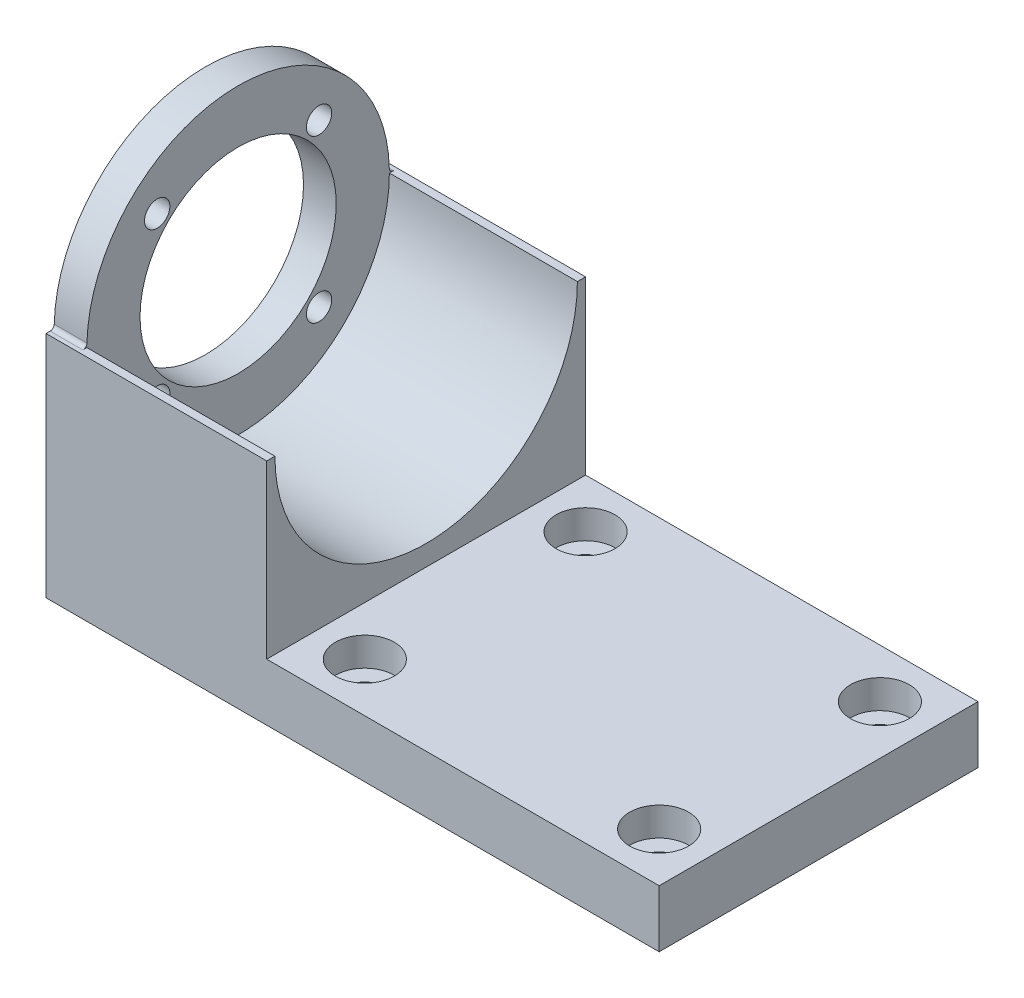
SolidWorks part; units mm, degrees
ref_plane "Plano frontal" through (0, 0, 0) normal (0, 0, 1) x (1, 0, 0)
ref_plane "Plano superior" through (0, 0, 0) normal (0, 1, 0) x (1, 0, 0)
ref_plane "Plano direito" through (0, 0, 0) normal (1, 0, 0) x (0, 0, -1)
sketch "Esboço1" plane through (0, 0, 0) normal (1, 0, 0) x (0, 0, -1)
  circle A0 centre (0, 0) radius 12
  circle A1 centre (0, 0) radius 18.5
  dimension "D1" = 24
  dimension "D2" = 37
extrude "Ressalto-extrusão1" add sketch "Esboço1" along normal blind 4
sketch "Esboço2" plane through (0, 0, 0) normal (-1, 0, 0) x (0, 0, 1)
  line L0 (-19.5, 0) -> (-19.5, -21)
  line L1 (-19.5, -21) -> (19.5, -21)
  line L2 (19.5, -21) -> (19.5, 0)
  line L5 (-19.5, 0) -> (-18.5, 0)
  line L6 (18.5, 0) -> (19.5, 0)
  arc A0 (-18.5, 0) -> (18.5, 0) centre (0, 0) ccw
  dimension "D2" = 37
  dimension "D1" = 39
  dimension "D3" = 21
  dimension "D4" = 1
extrude "Ressalto-extrusão2" add sketch "Esboço2" against normal blind 27
fillet "Filete1" radius 0.5 2 edges at (2, 0, 18.5) (2, 0, -18.5)
sketch "Esboço3" plane through (0, 0, 0) normal (-1, 0, 0) x (0, 0, 1)
  line L0 (19.5, -21) -> (19.5, 0) construction
  line L1 (-19.5, -21) -> (19.5, -21)
  line L2 (-19.5, -21) -> (-19.5, -28)
  line L3 (-19.5, -28) -> (19.5, -28)
  line L4 (19.5, -21) -> (19.5, -28)
  dimension "D1" = 7
extrude "Ressalto-extrusão3" add sketch "Esboço3" against normal blind 75
sketch "Esboço4" plane through (0, -21, 0) normal (0, 1, 0) x (1, 0, 0)
  line L0 (75, 19.5) -> (27, 19.5) construction
  line L1 (27, 19.5) -> (27, -19.5) construction
  circle A0 centre (33, 13.5) radius 1.55
  circle A1 centre (69, 13.5) radius 1.55
  circle A2 centre (33, -13.5) radius 1.55
  circle A3 centre (69, -13.5) radius 1.55
  dimension "D1" = 3.1
  dimension "D2" = 6
  dimension "D3" = 6
  dimension "D4" = 2
  dimension "D5" = 2
extrude "Corte-extrusão1" cut sketch "Esboço4" against normal up to surface (7 mm away) up to face at (37.5, -28, 0)
sketch "Esboço5" plane through (0, -21, 0) normal (0, 1, 0) x (1, 0, 0)
  circle A0 centre (33, 13.5) radius 3.6
  circle A1 centre (69, 13.5) radius 3.6
  circle A2 centre (69, -13.5) radius 3.6
  circle A3 centre (33, -13.5) radius 3.6
  point P3 (0, 0)
  point P4 (0, 0)
  dimension "D1" = 7.2
  dimension "D4" = 27
  dimension "D5" = 36
  dimension "D2" = 2
  dimension "D3" = 2
extrude "Corte-extrusão2" cut sketch "Esboço5" against normal blind 3.5
sketch "Esboço6" plane through (0, 0, 0) normal (-1, 0, 0) x (0, 0, 1)
  line L0 (0, 0) -> (23.4221, 0) construction
  line L1 (9.8995, 9.8995) -> (0, 0) construction
  circle A0 centre (9.8995, 9.8995) radius 1.55
  circle A1 centre (9.8995, -9.8995) radius 1.55
  circle A2 centre (-9.8995, -9.8995) radius 1.55
  circle A3 centre (-9.8995, 9.8995) radius 1.55
  point P14 (0, 0)
  dimension "D2" = 3.1
  dimension "D1" = 14
  dimension "D3" = 45
  dimension "D4" = 4
extrude "Corte-extrusão4" cut sketch "Esboço6" against normal up to surface (4 mm away) from surface at 0 up to face at (4, 0.0473, 0) starting at face at (0, -4.652, 0)
